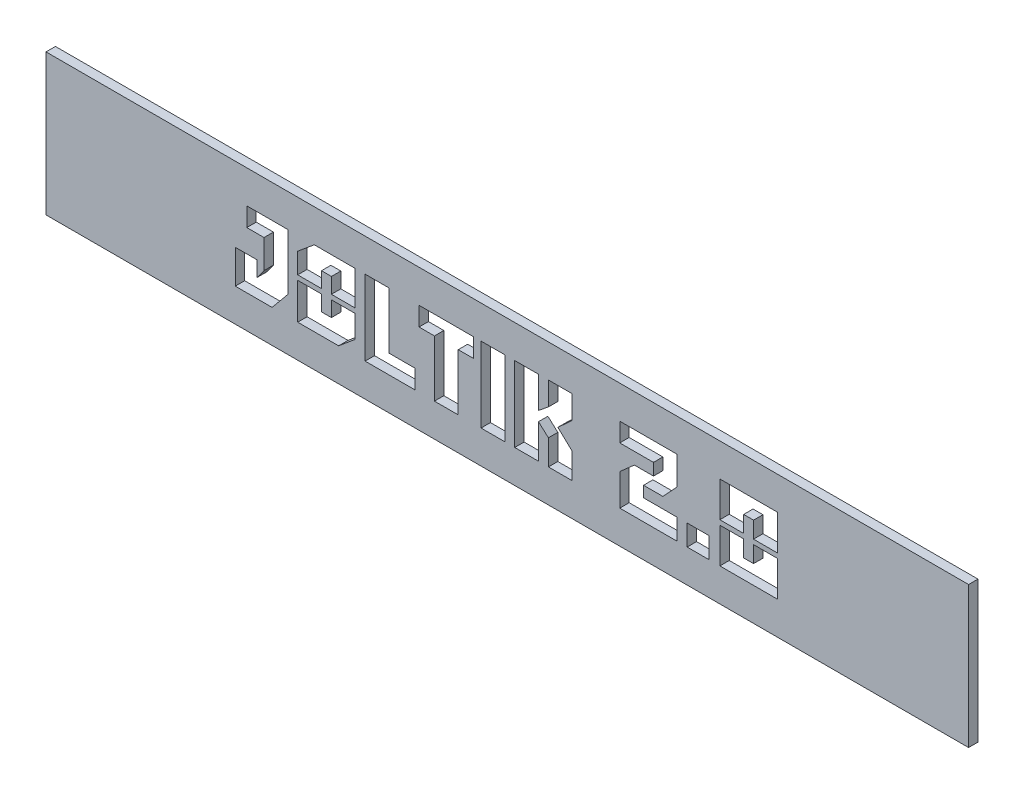
SolidWorks part; units mm, degrees
ref_plane "Front Plane" through (0, 0, 0) normal (0, 0, 1) x (1, 0, 0)
ref_plane "Top Plane" through (0, 0, 0) normal (0, 1, 0) x (1, 0, 0)
ref_plane "Right Plane" through (0, 0, 0) normal (1, 0, 0) x (0, 0, -1)
sketch "Sketch1" plane through (0, 0, 0) normal (0, 0, 1) x (1, 0, 0)
  line L0 (49, -29.5167) -> (49, 15.8392) construction
  line L1 (-49, 15.8392) -> (49, 15.8392)
  line L2 (-49, 15.8392) -> (-49, 0.8392)
  line L3 (-49, 0.8392) -> (49, 0.8392)
  line L4 (49, 15.8392) -> (49, 0.8392)
  line L5 (-49, 3.2752) -> (49, 3.2752) construction
  line L6 (-49, 8.3392) -> (49, 7.8392) construction
  text T0 "JOLTIK 2.0\r\n" font "a_Simpler" height in points 36
  dimension "D1" = 15
extrude "Boss-Extrude1" add sketch "Sketch1" along normal blind 1 contours L4 L1 L2 L3
sketch "Sketch2" plane through (0, 0, 1) normal (0, 0, 1) x (1, 0, 0)
  line L0 (-49, 8.3392) -> (49, 8.3392) construction
  line L1 (-49, 15.8392) -> (-49, 0.8392) construction
  line L2 (49, 15.8392) -> (49, 0.8392) construction
  line L3 (-49, 4.3392) -> (49, 4.3392) construction
  text T0 "JOLTIK 2.0\r\n" font "a_Simpler" height 8
  dimension "D1" = 4
extrude "Cut-Extrude1" cut sketch "Sketch2" against normal blind 10
sketch "Sketch3" plane through (0, 0, 1) normal (0, 0, 1) x (1, 0, 0)
  line L21 (-22.2632, 4.3392) -> (-19.7368, 6.5497) construction
  line L33 (-19.0769, 8.9245) -> (-19.0769, 8.4053)
  line L43 (-22.2632, 4.3392) -> (-22.2632, 10.8704) construction
  line L44 (-22.2632, 8.4444) -> (-16.1579, 8.4444) construction
  line L45 (-16.1579, 12.3392) -> (-16.1579, 5.8079) construction
  line L46 (-22.2632, 8.1944) -> (-16.1579, 8.1944)
  line L47 (-22.2632, 8.1944) -> (-22.2632, 8.6944)
  line L48 (-22.2632, 8.6944) -> (-16.1579, 8.6944)
  line L49 (-16.1579, 8.1944) -> (-16.1579, 8.6944)
  line L50 (-22.2632, 8.1944) -> (-16.1579, 8.6944) construction
  line L51 (-22.2632, 8.6944) -> (-16.1579, 8.1944) construction
  line L53 (28.6842, 12.3392) -> (28.6842, 4.3392) construction
  line L54 (28.6842, 8.3392) -> (22.5789, 8.3392) construction
  line L55 (22.5789, 4.3392) -> (22.5789, 12.3392) construction
  line L56 (22.5789, 8.0892) -> (28.6842, 8.0892)
  line L57 (22.5789, 8.0892) -> (22.5789, 8.5892)
  line L58 (22.5789, 8.5892) -> (28.6842, 8.5892)
  line L59 (28.6842, 8.0892) -> (28.6842, 8.5892)
  line L60 (22.5789, 8.0892) -> (28.6842, 8.5892) construction
  line L61 (22.5789, 8.5892) -> (28.6842, 8.0892) construction
  point P4 (-19.2105, 8.4444)
  point P17 (25.6316, 8.3392)
  dimension "D1" = 0.5
  dimension "D2" = 0.5
extrude "Boss-Extrude2" add sketch "Sketch3" against normal up to surface (1 mm away) up to face at (-19.2105, 8.3392, 0)
